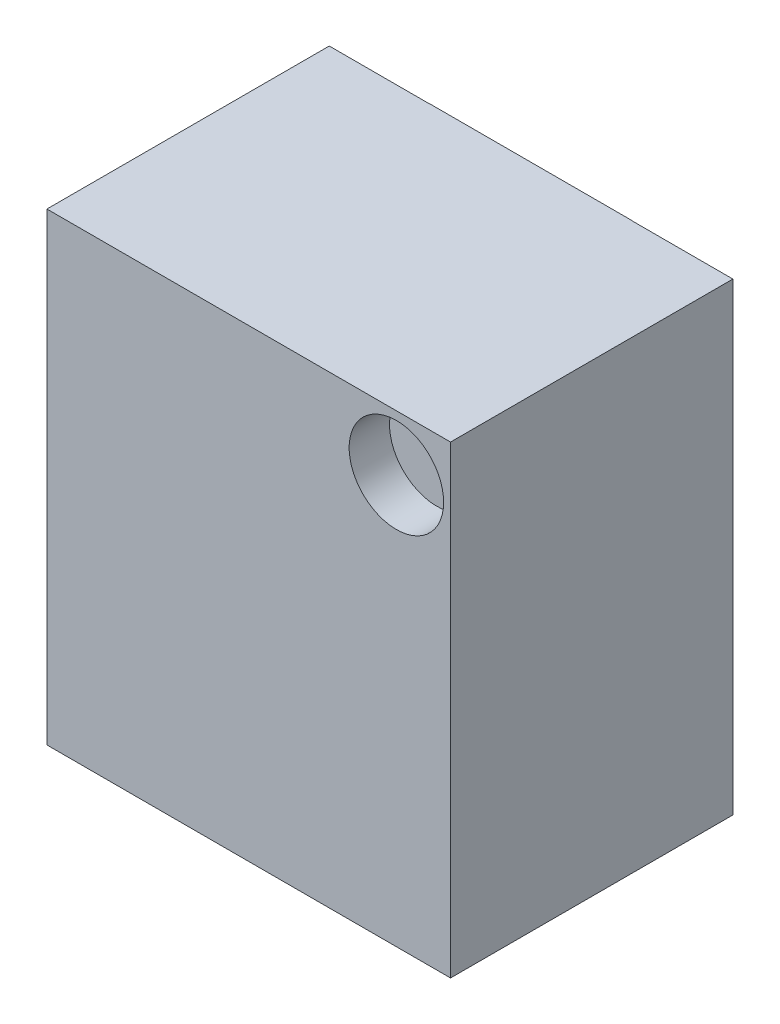
SolidWorks part; units mm, degrees
ref_plane "Front Plane" through (0, 0, 0) normal (0, 0, 1) x (1, 0, 0)
ref_plane "Top Plane" through (0, 0, 0) normal (0, 1, 0) x (1, 0, 0)
ref_plane "Right Plane" through (0, 0, 0) normal (1, 0, 0) x (0, 0, -1)
sketch "Sketch1" plane through (0, 0, 0) normal (0, 0, 1) x (1, 0, 0)
  line L1 (-1, -1.15) -> (1, -1.15)
  line L2 (-1, -1.15) -> (-1, 1.15)
  line L3 (-1, 1.15) -> (1, 1.15)
  line L4 (1, -1.15) -> (1, 1.15)
  line L5 (-1, -1.15) -> (1, 1.15) construction
  line L6 (-1, 1.15) -> (1, -1.15) construction
  point P0 (0, 0)
  dimension "D1" = 2.3
  dimension "D2" = 2
extrude "Boss-Extrude1" add sketch "Sketch1" along normal blind 1.4
sketch "Sketch2" plane through (0, 0, 1.4) normal (0, 0, 1) x (1, 0, 0)
  circle A0 centre (0.7316, 0.8744) radius 0.2341
  point P2 (-0.7236, 0.8573)
  point P3 (0.7316, 0.8744)
extrude "Cut-Extrude1" cut sketch "Sketch2" against normal blind 0.2
sketch "Sketch3" plane through (0, 0, 0) normal (0, 0, -1) x (-1, 0, 0)
  line L1 (-1, 1.15) -> (-0.5, 1.15)
  line L2 (-1, 1.15) -> (-1, 0.65)
  line L3 (-1, 0.65) -> (-0.5, 0.65)
  line L4 (-0.5, 1.15) -> (-0.5, 0.65)
  line L5 (1, 1.15) -> (0.5, 1.15)
  line L6 (1, 1.15) -> (1, 0.65)
  line L7 (1, 0.65) -> (0.5, 0.65)
  line L8 (0.5, 1.15) -> (0.5, 0.65)
  line L9 (-1, -1.15) -> (-0.5, -1.15)
  line L10 (-1, -1.15) -> (-1, -0.65)
  line L11 (-1, -0.65) -> (-0.5, -0.65)
  line L12 (-0.5, -1.15) -> (-0.5, -0.65)
  line L13 (1, -1.15) -> (0.5, -1.15)
  line L14 (1, -1.15) -> (1, -0.65)
  line L15 (1, -0.65) -> (0.5, -0.65)
  line L16 (0.5, -1.15) -> (0.5, -0.65)
  dimension "D1" = 0.5
  dimension "D2" = 0.5
  dimension "D3" = 0.5
extrude "Cut-Extrude2" cut sketch "Sketch3" against normal blind 0.001
